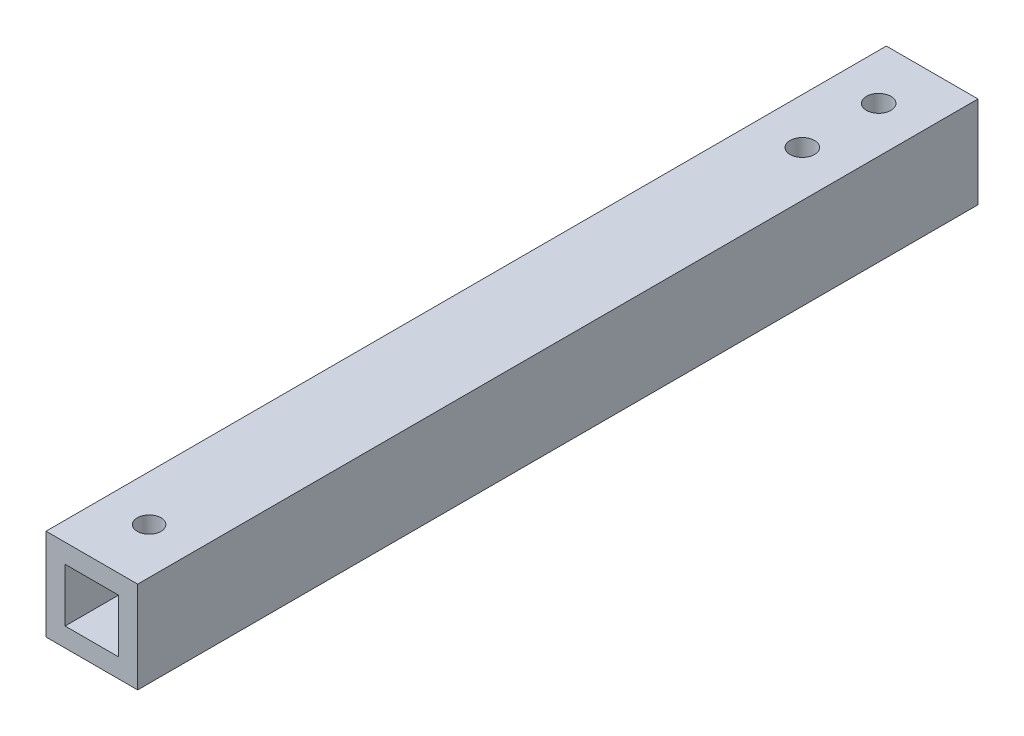
SolidWorks part; units mm, degrees
ref_plane "前视基准面" through (0, 0, 0) normal (0, 0, 1) x (1, 0, 0)
ref_plane "上视基准面" through (0, 0, 0) normal (0, 1, 0) x (1, 0, 0)
ref_plane "右视基准面" through (0, 0, 0) normal (1, 0, 0) x (0, 0, -1)
other "Configuration Table"
sketch "草图1" plane through (0, 0, 0) normal (0, 0, 1) x (1, 0, 0)
  line L1 (-6, -6) -> (6, -6)
  line L2 (-6, -6) -> (-6, 6)
  line L3 (-6, 6) -> (6, 6)
  line L4 (6, -6) -> (6, 6)
  line L5 (-6, -6) -> (6, 6) construction
  line L6 (-6, 6) -> (6, -6) construction
  point P0 (0, 0)
  dimension "D1" = 12
  dimension "D2" = 12
extrude "凸台-拉伸1" add sketch "草图1" along normal blind 110
sketch "草图2" plane through (0, 0, 110) normal (0, 0, 1) x (1, 0, 0)
  line L1 (3.5, -3.5) -> (-3.5, -3.5)
  line L2 (3.5, -3.5) -> (3.5, 3.5)
  line L3 (3.5, 3.5) -> (-3.5, 3.5)
  line L4 (-3.5, -3.5) -> (-3.5, 3.5)
  line L5 (3.5, -3.5) -> (-3.5, 3.5) construction
  line L6 (3.5, 3.5) -> (-3.5, -3.5) construction
  point P0 (0, 0)
  dimension "D1" = 7
  dimension "D2" = 7
extrude "切除-拉伸1" cut sketch "草图2" against normal through all
sketch "草图3" plane through (0, -6, 0) normal (0, -1, 0) x (1, 0, 0)
  line L0 (0, 0) -> (0, 110) construction
  line L1 (-6, 0) -> (6, 0) construction
  line L2 (-6, 110) -> (6, 110) construction
  circle A0 centre (0, 7) radius 1.6
  circle A1 centre (0, 17) radius 1.6
  circle A2 centre (0, 102.5) radius 1.55
  dimension "D1" = 3.2
  dimension "D5" = 3.1
  dimension "D2" = 7
  dimension "D4" = 10
  dimension "D6" = 7.5
  dimension "D3" = 2
extrude "切除-拉伸2" cut sketch "草图3" against normal through all
